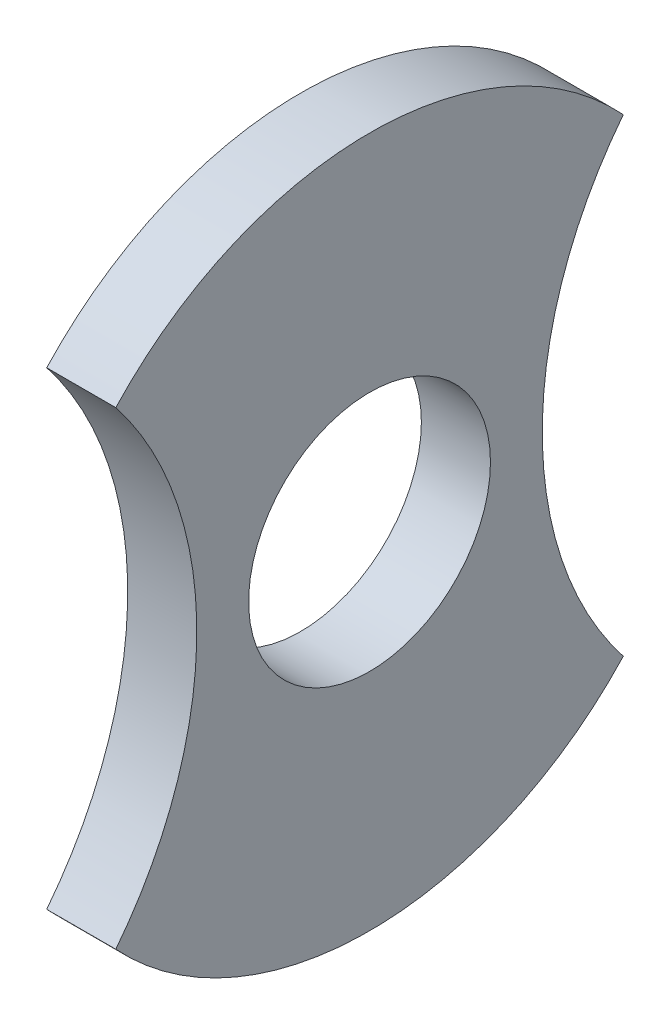
SolidWorks part; units mm, degrees
ref_plane "Front Plane" through (0, 0, 0) normal (0, 0, 1) x (1, 0, 0)
ref_plane "Top Plane" through (0, 0, 0) normal (0, 1, 0) x (1, 0, 0)
ref_plane "Right Plane" through (0, 0, 0) normal (1, 0, 0) x (0, 0, -1)
sketch "Sketch1" plane through (0, 0, 0) normal (1, 0, 0) x (0, 0, -1)
  line L0 (0, 0) -> (-25, 0) construction
  line L1 (0, 50.0063) -> (0, -50) construction
  line L2 (0, 50.0063) -> (-25, 50.0063) construction
  line L3 (-25, 50.0063) -> (-25, 0) construction
  arc A1 (-36.7227, 33.9422) -> (-25, 0) centre (-80, 0) cw
  arc A2 (-36.7227, 33.9422) -> (36.7227, 33.9422) centre (0, 0) cw
  arc A3 (36.7227, 33.9422) -> (25, 0) centre (80, 0) ccw
  arc A4 (36.7227, -33.9422) -> (25, 0) centre (80, 0) cw
  arc A5 (-36.7227, -33.9422) -> (36.7227, -33.9422) centre (0, 0) ccw
  arc A6 (-36.7227, -33.9422) -> (-25, 0) centre (-80, 0) ccw
  circle A7 centre (0, 0) radius 50.0063 construction
  dimension "D2" = 55
  dimension "D3" = 25
extrude "Boss-Extrude1" add sketch "Sketch1" along normal blind 10
sketch "Sketch3" plane through (0, 0, 0) normal (1, 0, 0) x (0, 0, -1)
  circle A0 centre (0, 0) radius 17.5
  dimension "D1" = 35
extrude "Cut-Extrude3" cut sketch "Sketch3" along normal through all
